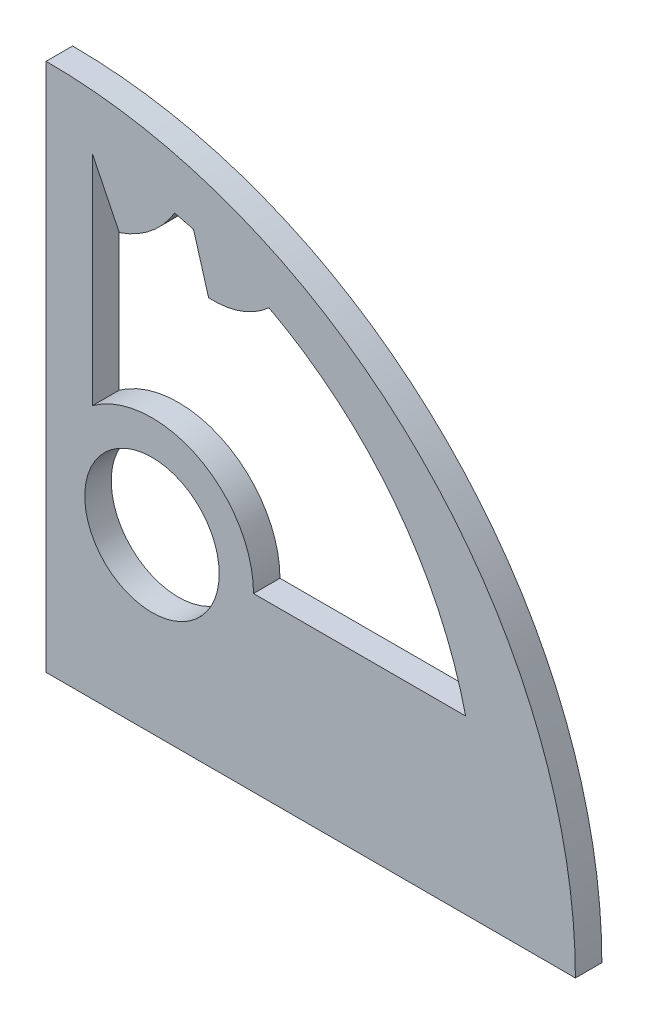
SolidWorks part; units mm, degrees
ref_plane "Alzado" through (0, 0, 0) normal (0, 0, 1) x (1, 0, 0)
ref_plane "Planta" through (0, 0, 0) normal (0, 1, 0) x (1, 0, 0)
ref_plane "Vista lateral" through (0, 0, 0) normal (1, 0, 0) x (0, 0, -1)
sketch "Croquis1" plane through (0, 0, 0) normal (0, 0, 1) x (1, 0, 0)
  line L0 (0, 100) -> (0, 0)
  line L1 (0, 0) -> (100, 0)
  arc A0 (100, 0) -> (0, 100) centre (0, 0) ccw
  dimension "D1" = 100
extrude "Saliente-Extruir1" add sketch "Croquis1" along normal blind 5
sketch "Croquis2" plane through (0, 0, 5) normal (0, 0, 1) x (1, 0, 0)
  line L0 (0, 0) -> (100, 0) construction
  line L3 (0, 100) -> (0, 0) construction
  circle A0 centre (20, 32.5) radius 12.7
  point P6 (0, 32.9664)
  point P7 (-9.2746, 33.5634)
  dimension "D1" = 32.5
  dimension "D2" = 20
  dimension "D3" = 25.4
extrude "Cortar-Extruir1" cut sketch "Croquis2" against normal blind 10
sketch "Croquis3" plane through (0, 0, 5) normal (0, 0, 1) x (1, 0, 0)
  line L0 (8.7888, 48.0632) -> (8.7888, 89.1526)
  line L1 (39.1809, 32.5) -> (79.2583, 32.5)
  line L2 (8.7888, 89.1526) -> (13.8262, 78.8752)
  line L3 (27.856, 86.3994) -> (30.6977, 76.6552)
  arc A0 (39.1809, 32.5) -> (8.7888, 48.0632) centre (20, 32.5) ccw
  arc A1 (24.2822, 87.3126) -> (27.856, 86.3994) centre (7.952, 15.9574) cw
  arc A2 (13.8262, 78.8752) -> (24.2822, 87.3126) centre (7.6034, 97.2843) ccw
  arc A3 (30.6977, 76.6552) -> (42.0848, 80.7123) centre (31.587, 92.1678) ccw
  arc A4 (42.0848, 80.7123) -> (79.2583, 32.5) centre (7.952, 15.9574) cw
extrude "Cortar-Extruir2" cut sketch "Croquis3" against normal blind 10
